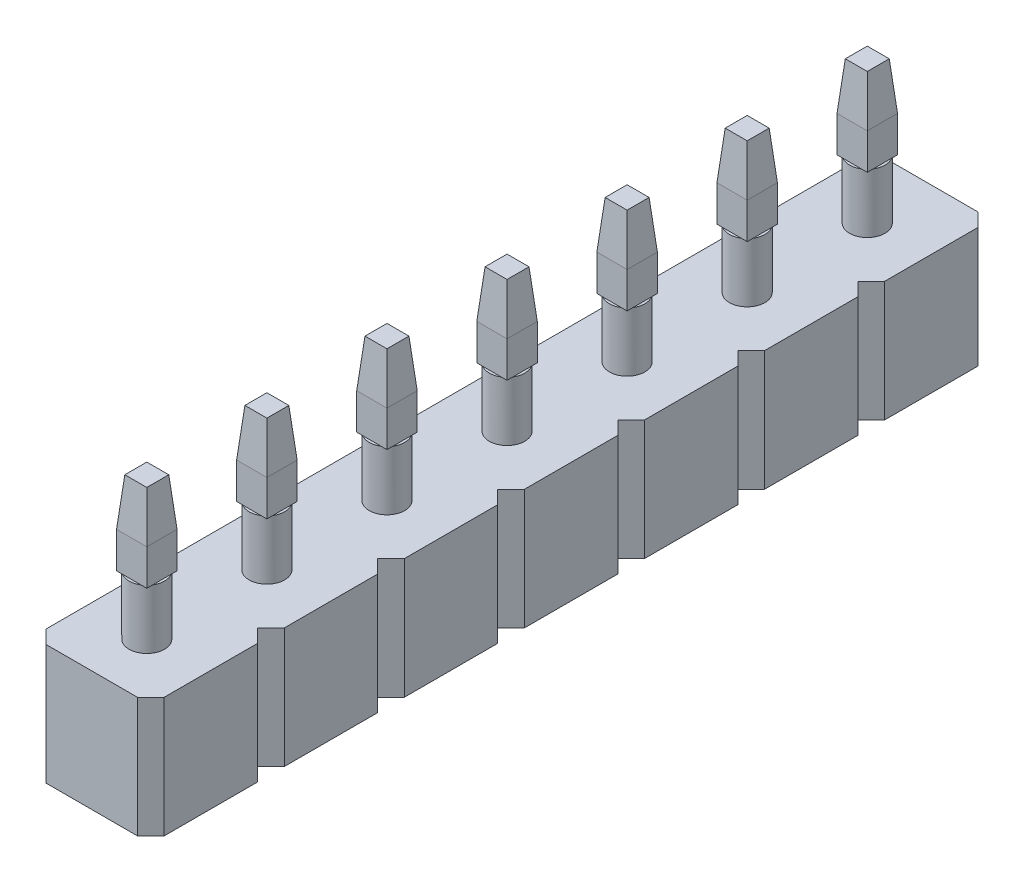
SolidWorks part; units mm, degrees
ref_plane "Front Plane" through (0, 0, 0) normal (0, 0, 1) x (1, 0, 0)
ref_plane "Top Plane" through (0, 0, 0) normal (0, 1, 0) x (1, 0, 0)
ref_plane "Right Plane" through (0, 0, 0) normal (1, 0, 0) x (0, 0, -1)
sketch "Sketch1" plane through (0, 0, 0) normal (0, 1, 0) x (1, 0, 0)
  line L0 (0, 0) -> (2.5, 0)
  line L1 (2.5, 0) -> (2.5, 2.54)
  line L2 (2.5, 2.54) -> (0, 2.54)
  line L3 (0, 2.54) -> (0, 0)
  dimension "D1" = 2.5
  dimension "D2" = 2.54
extrude "Boss-Extrude1" add sketch "Sketch1" along normal blind 2.54
sketch "Sketch3" plane through (0, 2.54, 0) normal (0, 1, 0) x (1, 0, 0)
  line L0 (2.5, 0) -> (2.5, 2.54) construction
  line L1 (2.5, 2.54) -> (0, 2.54) construction
  circle A0 centre (1.25, 1.165) radius 0.375
  dimension "D1" = 0.75
  dimension "D2" = 1.25
  dimension "D3" = 1.375
extrude "Boss-Extrude2" add sketch "Sketch3" along normal blind 1.25
sketch "Sketch4" plane through (0, 3.79, 0) normal (0, 1, 0) x (1, 0, 0)
  line L1 (0.93, 0.845) -> (1.57, 0.845)
  line L2 (0.93, 0.845) -> (0.93, 1.485)
  line L3 (0.93, 1.485) -> (1.57, 1.485)
  line L4 (1.57, 0.845) -> (1.57, 1.485)
  line L5 (0.93, 0.845) -> (1.57, 1.485) construction
  line L6 (0.93, 1.485) -> (1.57, 0.845) construction
  point P0 (1.25, 1.165)
  dimension "D1" = 0.64
extrude "Boss-Extrude3" add sketch "Sketch4" along normal blind 1.76
sketch "Sketch5" plane through (0, 2.54, 0) normal (0, 1, 0) x (1, 0, 0)
  line L0 (0.2828, 2.54) -> (0, 2.2572)
  line L1 (2.5, 2.54) -> (0, 2.54) construction
  line L2 (0, 2.54) -> (0, 0) construction
  line L3 (0, 2.2572) -> (0, 2.54)
  line L4 (0, 2.54) -> (0.2828, 2.54)
  line L5 (2.5, 2.54) -> (2.5, 2.2572)
  line L6 (2.5, 0) -> (2.5, 2.54) construction
  line L7 (2.5, 2.2572) -> (2.2172, 2.54)
  line L8 (2.2172, 2.54) -> (2.5, 2.54)
  line L9 (2.5, 0) -> (2.5, 0.2828)
  line L10 (2.5, 0.2828) -> (2.2172, 0)
  line L11 (0, 0) -> (2.5, 0) construction
  line L12 (2.2172, 0) -> (2.5, 0)
  line L13 (0, 0) -> (0, 0.2828)
  line L14 (0, 0.2828) -> (0.2828, 0)
  line L15 (0.2828, 0) -> (0, 0)
  dimension "D1" = 135
  dimension "D2" = 135
  dimension "D3" = 135
  dimension "D4" = 0.4
  dimension "D5" = 0.4
  dimension "D6" = 0.4
  dimension "D7" = 0.4
extrude "Cut-Extrude1" cut sketch "Sketch5" against normal up to surface (2.54 mm away) up to face at (1.25, 0, -1.27)
pattern_linear "LPattern5" count 7 spacing 2.54 along (0, 0, -1) of "Boss-Extrude1", "Boss-Extrude2", "Boss-Extrude3", "Cut-Extrude1"
chamfer "Chamfer3" distance 1 angle 5 28 edges at (1.25, 5.55, -16.085) (0.93, 5.55, -16.405) (1.25, 5.55, -16.725) (1.57, 5.55, -16.405) (1.25, 5.55, -13.545) (0.93, 5.55, -13.865) (1.25, 5.55, -14.185) (1.57, 5.55, -13.865) (1.25, 5.55, -11.005) (0.93, 5.55, -11.325) (1.25, 5.55, -11.645) (1.57, 5.55, -11.325) (1.25, 5.55, -8.465) (0.93, 5.55, -8.785) (1.25, 5.55, -9.105) (1.57, 5.55, -8.785) (1.25, 5.55, -5.925) (0.93, 5.55, -6.245) (1.25, 5.55, -6.565) (1.57, 5.55, -6.245) (1.25, 5.55, -3.385) (0.93, 5.55, -3.705) (1.25, 5.55, -4.025) (1.57, 5.55, -3.705) (1.25, 5.55, -0.845) (0.93, 5.55, -1.165) (1.25, 5.55, -1.485) (1.57, 5.55, -1.165)
